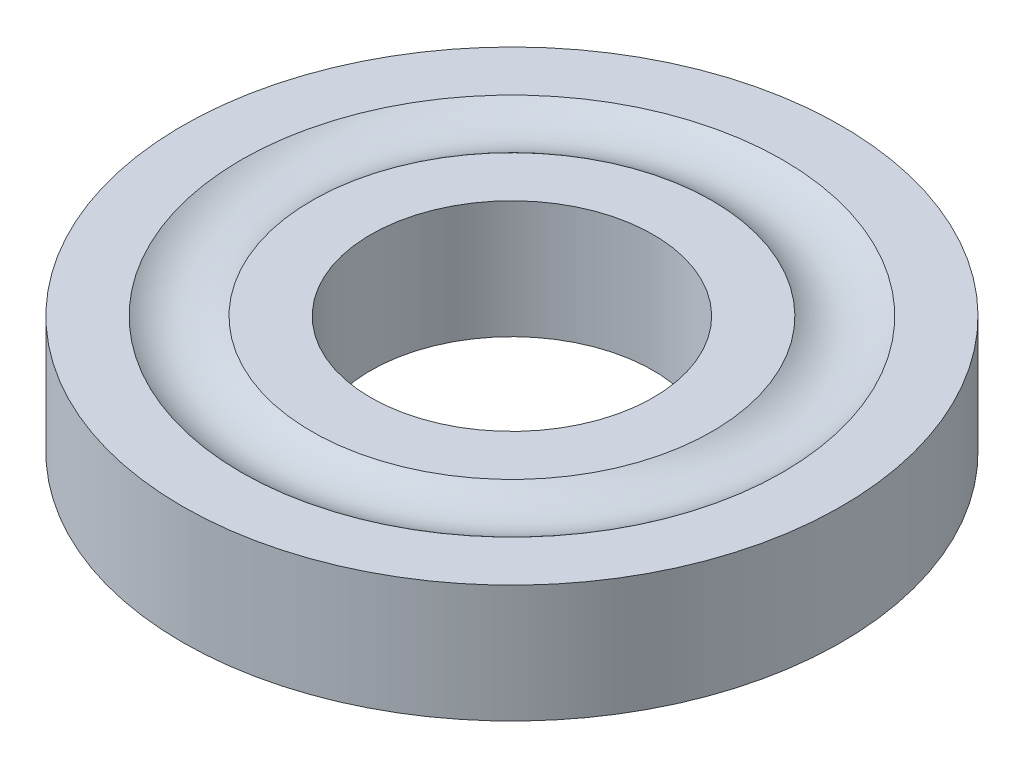
SolidWorks part; units mm, degrees
ref_plane "Front Plane" through (0, 0, 0) normal (0, 0, 1) x (1, 0, 0)
ref_plane "Top Plane" through (0, 0, 0) normal (0, 1, 0) x (1, 0, 0)
ref_plane "Right Plane" through (0, 0, 0) normal (1, 0, 0) x (0, 0, -1)
sketch "Sketch1" plane through (0, 0, 0) normal (0, 1, 0) x (1, 0, 0)
  circle A0 centre (0, 0) radius 3.5
  circle A1 centre (0, 0) radius 1.5
  dimension "D1" = 3
  dimension "D2" = 7
extrude "Boss-Extrude1" add sketch "Sketch1" along normal blind 1.25
sketch "Sketch2" plane through (0, 0, 0) normal (0, 0, 1) x (1, 0, 0)
  line L0 (-1.5, 1.25) -> (-3.5, 1.25) construction
  line L1 (-2.5, 1.25) -> (-2.5, 1.75) construction
  line L2 (-3.2744, 1.125) -> (-1.7055, 1.125) construction
  line L3 (0, 0) -> (0, 2.841) construction
  circle A0 centre (-2.5, 1.75) radius 0.625
  dimension "D1" = 1.25
  dimension "D2" = 0.125
revolve "Cut-Revolve1" cut sketch "Sketch2" angle 360 about L3
